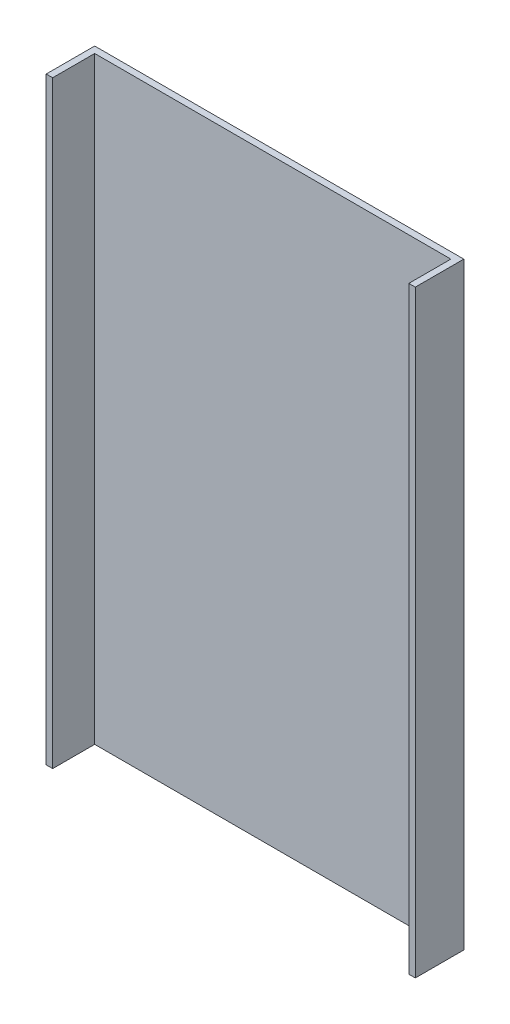
SolidWorks part; units mm, degrees
ref_plane "Front Plane" through (0, 0, 0) normal (0, 0, 1) x (1, 0, 0)
ref_plane "Top Plane" through (0, 0, 0) normal (0, 1, 0) x (1, 0, 0)
ref_plane "Right Plane" through (0, 0, 0) normal (1, 0, 0) x (0, 0, -1)
sketch "Sketch1" plane through (0, 0, 0) normal (0, 0, 1) x (1, 0, 0)
  line L1 (0, 0) -> (72.46, 0)
  line L2 (0, 0) -> (0, 117.46)
  line L3 (0, 117.46) -> (72.46, 117.46)
  line L4 (72.46, 0) -> (72.46, 117.46)
  dimension "D1" = 72.46
  dimension "D2" = 117.46
extrude "Boss-Extrude1" add sketch "Sketch1" along normal blind 1.27
sketch "Sketch2" plane through (0, 0, 1.27) normal (0, 0, 1) x (1, 0, 0)
  line L0 (0, 0) -> (72.46, 0) construction
  line L1 (0, 117.46) -> (1.27, 117.46)
  line L2 (0, 117.46) -> (0, 0)
  line L3 (0, 0) -> (1.27, 0)
  line L4 (1.27, 117.46) -> (1.27, 0)
  line L5 (72.46, 117.46) -> (0, 117.46) construction
  line L6 (72.46, 0) -> (71.19, 0)
  line L7 (72.46, 0) -> (72.46, 117.46)
  line L8 (72.46, 117.46) -> (71.19, 117.46)
  line L9 (71.19, 0) -> (71.19, 117.46)
  dimension "D1" = 1.27
  dimension "D2" = 1.27
extrude "Boss-Extrude2" add sketch "Sketch2" along normal blind 8.25
